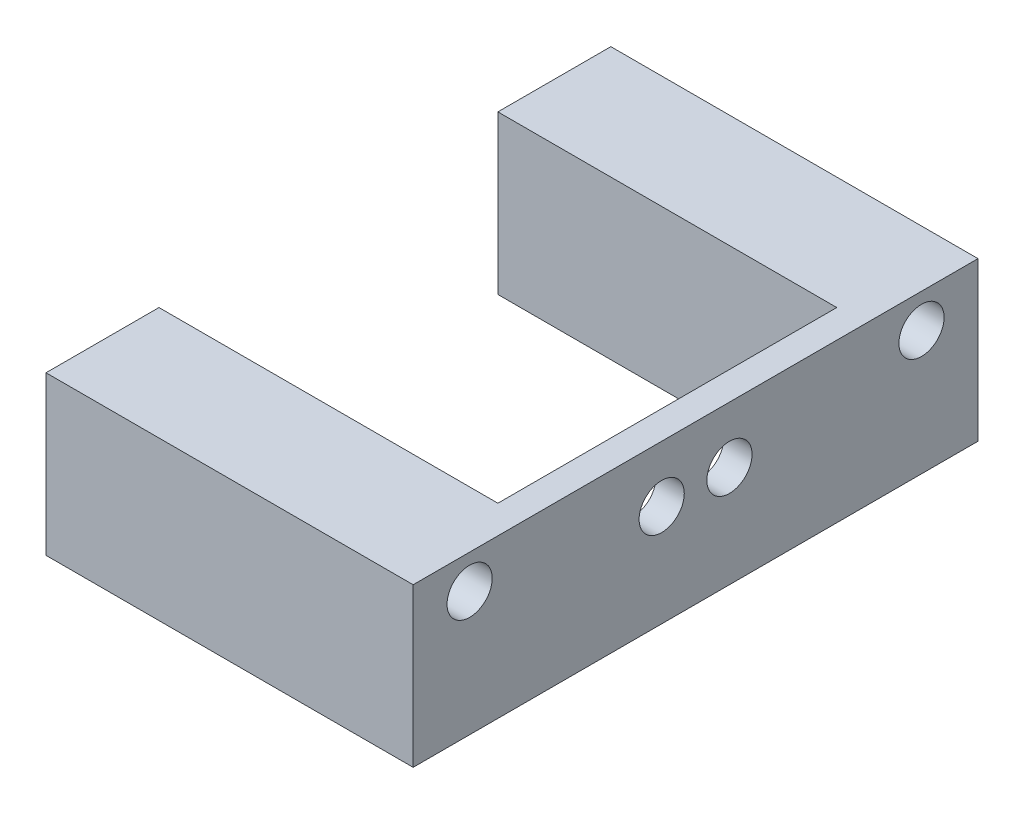
SolidWorks part; units mm, degrees
ref_plane "Front Plane" through (0, 0, 0) normal (0, 0, 1) x (1, 0, 0)
ref_plane "Top Plane" through (0, 0, 0) normal (0, 1, 0) x (1, 0, 0)
ref_plane "Right Plane" through (0, 0, 0) normal (1, 0, 0) x (0, 0, -1)
sketch "Sketch1" plane through (0, 0, 0) normal (1, 0, 0) x (0, 0, -1)
  line L0 (-50, 0) -> (50, 0)
  line L1 (50, -14) -> (-50, -14)
  line L2 (50, -14) -> (50, 14)
  line L3 (50, 14) -> (-50, 14)
  line L4 (-50, -14) -> (-50, 14)
  line L5 (50, -14) -> (-50, 14) construction
  line L6 (50, 14) -> (-50, -14) construction
  line L7 (0, 14) -> (0, -14)
  line L8 (-50, 8) -> (50, 8)
  line L9 (-40, 14) -> (-40, -14)
  line L10 (40, 14) -> (40, -14)
  line L11 (-50, 4) -> (50, 4)
  line L12 (-6, 14) -> (-6, -14)
  line L13 (6, 14) -> (6, -14)
  circle A0 centre (-40, 8) radius 4
  circle A1 centre (40, 8) radius 4
  circle A2 centre (-6, 4) radius 4
  circle A3 centre (6, 4) radius 4
  point P0 (0, 0)
  point P10 (-40, 14)
  point P11 (-50, 8)
  point P12 (40, 14)
  point P13 (50, 8)
  point P16 (-40, -14)
  point P17 (40, -14)
  point P20 (-40, 8)
  point P23 (40, 8)
  point P28 (-50, 4)
  point P29 (50, 4)
  point P30 (-6, 14)
  point P31 (6, 14)
  point P32 (-6, 4)
  point P39 (6, 4)
  dimension "D9" = 8
  dimension "D10" = 8
  dimension "D15" = 8
  dimension "D16" = 8
  dimension "D1" = 100
  dimension "D2" = 28
  dimension "D3" = 10
  dimension "D4" = 6
  dimension "D5" = 10
  dimension "D6" = 6
  dimension "D7" = 10
  dimension "D8" = 10
  dimension "D11" = 6
  dimension "D12" = 6
  dimension "D13" = 10
  dimension "D14" = 10
extrude "Boss-Extrude1" add sketch "Sketch1" along normal blind 5 contours A1 L8 L2 L3 L10 | A1 L10 L3 L13 L8 | L13 L3 L7 L8 | L3 L12 L8 L7 | A0 L8 L12 L3 L9 | A0 L9 L3 L4 L8 | A0 L8 L4 L11 | L11 L4 L0 L9 | L9 L0 L4 L1 | L12 L0 L9 L1 | A2 L11 L9 L0 | A2 L8 A0 L11 | L0 L12 L1 L7 | A3 L8 L7 L11 | A2 L11 L7 L8 | L13 L0 L7 L1 | A3 L11 L7 L0 | A2 L0 L7 L11 | A3 L0 L10 L11 | A3 L11 A1 L8 | L0 L13 L1 L10 | L0 L10 L1 L2 | L11 L10 L0 L2 | A1 L11 L2 L8
sketch "Sketch2" plane through (0, 0, 0) normal (-1, 0, 0) x (0, 0, 1)
  line L0 (-50, 14) -> (50, 14) construction
  line L1 (-50, -14) -> (50, -14) construction
  line L2 (-50, -14) -> (-50, 14) construction
  line L3 (-30, 14) -> (-30, -14)
  line L4 (30, 14) -> (30, -14)
  line L5 (30, -14) -> (50, -14)
  line L6 (50, -14) -> (50, 14)
  line L7 (50, 14) -> (30, 14)
  line L8 (-30, 14) -> (-50, 14)
  line L9 (-50, 14) -> (-50, -14)
  line L10 (-50, -14) -> (-30, -14)
  circle A0 centre (-40, 8) radius 4
  circle A2 centre (40, 8) radius 4
  point P0 (-30, 14)
  point P1 (30, 14)
  point P4 (-30, -14)
  point P5 (30, -14)
  dimension "D1" = 20
  dimension "D2" = 20
  dimension "D3" = 20
  dimension "D4" = 20
extrude "Boss-Extrude2" add sketch "Sketch2" along normal blind 60
